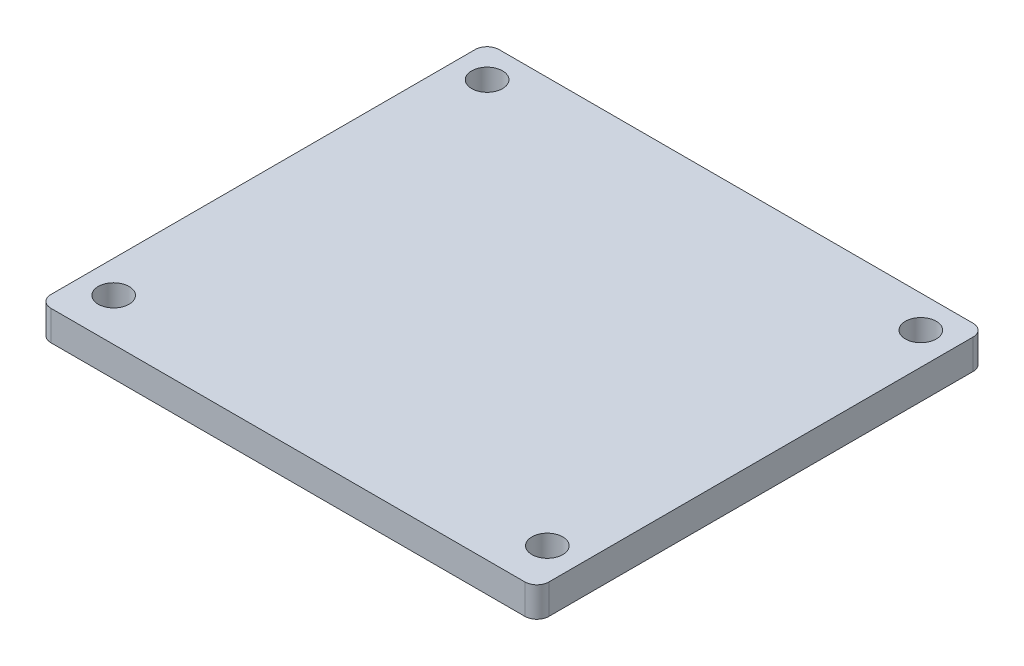
SolidWorks part; units mm, degrees
ref_plane "前基準面" through (0, 0, 0) normal (0, 0, 1) x (1, 0, 0)
ref_plane "上基準面" through (0, 0, 0) normal (0, 1, 0) x (1, 0, 0)
ref_plane "右基準面" through (0, 0, 0) normal (1, 0, 0) x (0, 0, -1)
sketch "草圖1" plane through (0, 0, 0) normal (0, 1, 0) x (1, 0, 0)
  line L1 (-23.8, -22.5) -> (23.8, -22.5)
  line L2 (-25, -21.3) -> (-25, 21.3)
  line L3 (-23.8, 22.5) -> (23.8, 22.5)
  line L4 (25, -21.3) -> (25, 21.3)
  line L5 (-25, -22.5) -> (25, 22.5) construction
  line L6 (-25, 22.5) -> (25, -22.5) construction
  arc A0 (-23.8, -22.5) -> (-25, -21.3) centre (-23.8, -21.3) cw
  arc A1 (23.8, -22.5) -> (25, -21.3) centre (23.8, -21.3) ccw
  arc A2 (23.8, 22.5) -> (25, 21.3) centre (23.8, 21.3) cw
  arc A3 (-25, 21.3) -> (-23.8, 22.5) centre (-23.8, 21.3) cw
  circle A4 centre (-21.775, 19.275) radius 1.55
  circle A5 centre (21.775, 19.275) radius 1.55
  circle A6 centre (21.775, -18.225) radius 1.55
  circle A7 centre (-21.775, -18.225) radius 1.55
  point P0 (0, 0)
  point P26 (-17.6277, 19.7628)
  point P27 (17.7223, 19.75)
  point P28 (-21.341, -15.5092)
  point P29 (-21.6741, 22.5)
  point P30 (21.4784, -14.2214)
  point P31 (0, 0)
  point P32 (0, 0)
  point P33 (0, 0)
  point P34 (0, 0)
  point P35 (0, 0)
  point P37 (15.3653, -16.3945)
  dimension "D3" = 1.2
  dimension "D4" = 3.1
  dimension "D1" = 45
  dimension "D2" = 50
  dimension "D5" = 3.225
  dimension "D6" = 3.225
  dimension "D7" = 4.275
  dimension "D8" = 3.225
extrude "填料-伸長1" add sketch "草圖1" along normal blind 3
